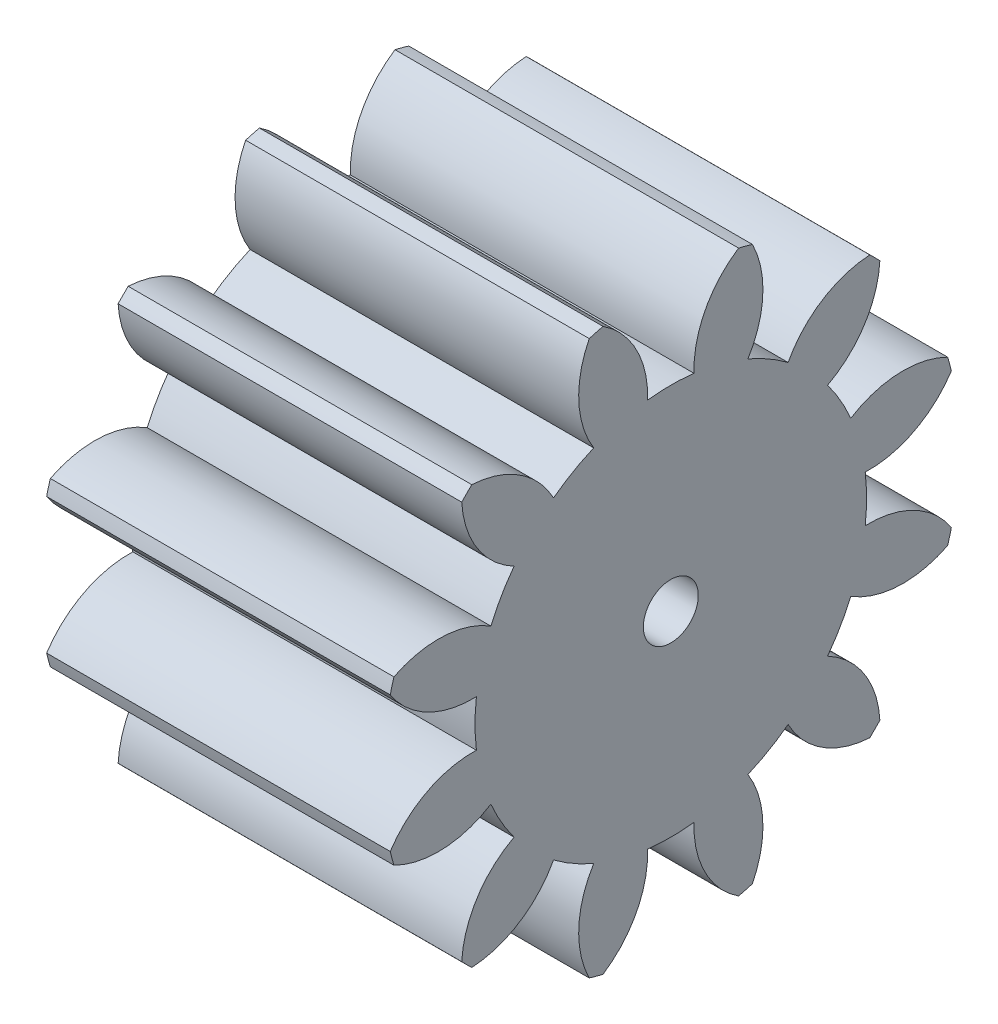
SolidWorks part; units mm, degrees
ref_plane "Plane1" through (0, 0, 0) normal (0, 0, 1) x (1, 0, 0)
ref_plane "Plane2" through (0, 0, 0) normal (0, 1, 0) x (1, 0, 0)
ref_plane "Plane3" through (0, 0, 0) normal (1, 0, 0) x (0, 0, -1)
other "Configuration Table"
sketch "HoldingSke" plane through (0, 0, 0) normal (0, 1, 0) x (1, 0, 0)
  line L0 (0, 0) -> (1.6302, -0.3465)
  line L1 (-15, 0) -> (100, 0) construction
  line L2 (0, 0) -> (-2.1039, 2.3779)
  line L3 (0, 0) -> (-11.863, 4.5341)
  line L4 (0, 0) -> (8.4473, 1.7955)
  line L5 (0, 0) -> (-46.8476, -17.4728)
  line L6 (0, 0) -> (-4.1448, -2.7965)
  line L7 (-2.1039, 2.3779) -> (8.6586, 51.2059)
  line L8 (-76.2, 54.61) -> (-76.1, 54.61)
  line L9 (-71.009, 38.7566) -> (-53.1078, 45.2721)
  line L10 (-76.2, 71.12) -> (104.1128, 71.12)
  line L11 (0, 0) -> (-5, 0)
  line L12 (-76.2, 101.6) -> (-76.177, 101.6)
  line L13 (24.9733, 27.94) -> (52.9518, 28.4284)
  line L14 (24.9733, 27.94) -> (24.9743, 27.94)
  line L15 (24.9733, 27.94) -> (100.4006, 29.5858)
  line L16 (-63.627, -0.6) -> (-12.827, -0.6)
  circle A0 centre (0, 0) radius 0.4
  circle A1 centre (0, 0) radius 2.849
  circle A2 centre (0, 0) radius 37.5
  circle A3 centre (0, 0) radius 0.4
  dimension "MHD" = 5.698
  dimension "Hub_dia" = 75
  dimension "Bore" = 0.8
  dimension "MBD" = 0.8
  dimension "Num_teeth" = 12
  dimension "Pitch" = 1.6667
  dimension "Overall_len" = 50
  dimension "Show_teeth" = 12
  dimension "Thickness" = 5
  dimension "OAL" = 50.0001
  dimension "T_dim" = 0.1
  dimension "Ap" = 20
  dimension "H" = 19.05
  dimension "Pitch_radius" = 180.3128
  dimension "Width" = 5
  dimension "Backlash" = 0.023
  dimension "Addendum_fac" = 1
  dimension "Dedendum_fac" = 1.25
  dimension "Clearance_fac" = 0.25
  dimension "Dedendum_add" = 0.001
  dimension "Module" = 0.6
sketch "BasProSke" plane through (0, 0, 0) normal (0, 1, 0) x (1, 0, 0)
  line L0 (-10, 0) -> (60, 0) construction
  line L1 (0, 0) -> (0, 4.2)
  line L2 (0, 0) -> (5, 0)
  line L3 (5, 0) -> (5, 4.2)
  line L4 (5, 4.2) -> (0, 4.2)
  dimension "Thickness" = 5
  dimension "Diameter" = 8.4
revolve "Base-Revolve" add sketch "BasProSke" angle 360 about L0
sketch "TooCutSke" plane through (0, 0, 0) normal (1, 0, 0) x (0, 0, -1)
  line L1 (0, 0) -> (0, 107) construction
  line L2 (0, 0) -> (-0.5101, 3.5637) construction
  line L3 (0, 0) -> (-1.8502, 6.905) construction
  line L4 (-0.5101, 3.5637) -> (-0.9251, 3.4525) construction
  arc A0 (0.3376, 2.8289) -> (-0.3376, 2.8289) centre (0, 0) ccw
  arc A1 (1.0161, 4.1014) -> (-1.0161, 4.1014) centre (0, 0) ccw
  circle A2 centre (0, 0) radius 3.6 construction
  circle A3 centre (0, 0) radius 3.3829 construction
  arc A4 (-0.3376, 2.8289) -> (-1.0161, 4.1014) centre (-1.7768, 2.8787) ccw
  arc A5 (1.0161, 4.1014) -> (0.3376, 2.8289) centre (1.7768, 2.8787) ccw
  dimension "Root_dia" = 5.698
  dimension "Overcut_dia" = 8.4508
  dimension "Pitch_dia" = 7.2
  dimension "Base_dia" = 6.7658
  dimension "Flank_rad" = 1.44
  dimension "Half_ang" = 15
  dimension "Half_CT" = 0.4296
extrude "ToothCut" cut sketch "TooCutSke" along normal through all
fillet "Breaks" [suppressed] radius 0.012
fillet "RootFillets" [suppressed] radius 0.151
pattern_circular "TeethCuts" count 12 every 30 about axis through (-10, 0, 0) along (1, 0, 0) of "ToothCut", "RootFillets", "Breaks"
sketch "HubNeaOneSke" plane through (0, 0, 0) normal (-1, 0, 0) x (0, 0, 1)
  circle A0 centre (0, 0) radius 2.849
  dimension "Diameter" = 5.698
extrude "HubNearOne" [suppressed] add sketch "HubNeaOneSke" along normal blind 45.0001
sketch "HubNeaBotSke" plane through (0, 0, 0) normal (-1, 0, 0) x (0, 0, 1)
  circle A0 centre (0, 0) radius 2.849
  dimension "Diameter" = 5.698
extrude "HubNearBoth" [suppressed] add sketch "HubNeaBotSke" along normal blind 22.5
ref_plane "FarPln" through (5, 0, 0) normal (1, 0, 0) x (0, 0, -1)
sketch "HubFarSke" plane through (5, 0, 0) normal (1, 0, 0) x (0, 0, -1)
  circle A0 centre (0, 0) radius 2.849
  dimension "Diameter" = 5.698
extrude "HubFar" [suppressed] add sketch "HubFarSke" along normal blind 22.5
sketch "BorSke" plane through (0, 0, 0) normal (1, 0, 0) x (0, 0, -1)
  circle A0 centre (0, 0) radius 0.4
  dimension "Diameter" = 0.8
extrude "Bore" cut sketch "BorSke" along normal mid plane 100.0001
sketch "KeySke" plane through (0, 0, 0) normal (1, 0, 0) x (0, 0, -1)
  line L0 (-0.05, 0) -> (-0.05, 0.5)
  line L1 (-0.05, 0.5) -> (0.05, 0.5)
  line L2 (0.05, 0.5) -> (0.05, 0)
  line L3 (0, 0) -> (0, 34) construction
  line L4 (-0.05, 0) -> (0.05, 0)
  dimension "Offset" = 0.5
  dimension "Width" = 0.1
extrude "Keyway" [suppressed] cut sketch "KeySke" along normal mid plane 100.0001
pattern_circular "Keyway2" [suppressed] count 2 every 90 about axis through (-10, 0, 0) along (1, 0, 0)
equation "' \"Module@HoldingSke\" = 6.35"
equation "' \"Num_teeth@HoldingSke\" = 12"
equation "' \"Ap@HoldingSke\" =  20"
equation "' \"Ap@HoldingSke\" = 20"
equation "' \"Width@HoldingSke\" = 0.5 * 25.4"
equation "' \"Hub_dia@HoldingSke\"= 1 * 25.4"
equation "' \"Hub_dia@HoldingSke\" = 1 * 25.4"
equation "' \"Overall_len@HoldingSke\" = 1.0 * 25.4"
equation "' \"Bore@HoldingSke\" = 0.75 * 25.4"
equation "' \"T_dim@HoldingSke\" = 0.1 * 25.4"
equation "' \"Width@KeySke\" = 0.25 * 25.4"
equation "' \"Show_teeth@HoldingSke\" = 13"
equation "' \"Backlash@HoldingSke\" = 0.009 * 25.4"
equation "' \"Addendum_fac@HoldingSke\" = 1.0"
equation "' \"Dedendum_fac@HoldingSke\" = 1.25"
equation "' \"Dedendum_add@HoldingSke\" = 0.00005 * 25.4"
equation "' \"Clearance_fac@HoldingSke\" = 0.25"
equation "\"Pitch@HoldingSke\" = 1 / \"Module@HoldingSke\""
equation "\"Overcut_dia@TooCutSke\" = (\"Num_teeth@HoldingSke\" + 2 * \"Addendum_fac@HoldingSke\") / \"Pitch@HoldingSke\" + 0.002 * 25.4"
equation "\"Pitch_dia@TooCutSke\" = \"Num_teeth@HoldingSke\" / \"Pitch@HoldingSke\""
equation "\"Base_dia@TooCutSke\" = \"Num_teeth@HoldingSke\" / \"Pitch@HoldingSke\" * cos((\"Ap@HoldingSke\"  * 3.14159265 / 180))"
equation "\"Root_dia@TooCutSke\" = (\"Num_teeth@HoldingSke\" + 2) / \"Pitch@HoldingSke\" - 2 * (\"Addendum_fac@HoldingSke\" + \"Dedendum_fac@HoldingSke\") / \"Pitch@HoldingSke\" - \"Dedendum_add@HoldingSke\" * 2"
equation "\"Half_ang@TooCutSke\" = 180 / \"Num_teeth@HoldingSke\""
equation "\"Half_CT@TooCutSke\" = \"Num_teeth@HoldingSke\" / \"Pitch@HoldingSke\" * sin((3.14159265 / 2 / \"Num_teeth@HoldingSke\")) / 2 - 7 * \"Backlash@HoldingSke\" / 4"
equation "\"Flank_rad@TooCutSke\" = \"Num_teeth@HoldingSke\" / \"Pitch@HoldingSke\" / 5"
equation "\"Radius@RootFillets\" = \"Clearance_fac@HoldingSke\" / \"Pitch@HoldingSke\" + \"Dedendum_add@HoldingSke\""
equation "\"Break_rad@Breaks\" = 0.02 / \"Pitch@HoldingSke\""
equation "\"Thickness@HoldingSke\" = \"Width@HoldingSke\""
equation "\"OAL@HoldingSke\" = \"Thickness@HoldingSke\""
equation "\"MHD@HoldingSke\" = (\"Num_teeth@HoldingSke\" + 2) / \"Pitch@HoldingSke\" - 2 * (\"Addendum_fac@HoldingSke\" + \"Dedendum_fac@HoldingSke\")  / \"Pitch@HoldingSke\" - \"Dedendum_add@HoldingSke\" * 2"
equation "\"MBD@HoldingSke\" = (\"Num_teeth@HoldingSke\" + 2) / \"Pitch@HoldingSke\" - 2 * (\"Addendum_fac@HoldingSke\" + \"Dedendum_fac@HoldingSke\")  / \"Pitch@HoldingSke\" - \"Dedendum_add@HoldingSke\" * 2 - 0.002 * 25.4"
equation "\"MHD@HoldingSke\" = ((sgn( \"MHD@HoldingSke\" - \"Hub_dia@HoldingSke\" )-1)*( \"MHD@HoldingSke\" - \"Hub_dia@HoldingSke\" ))/-2+ \"Hub_dia@HoldingSke\""
equation "\"MBD@HoldingSke\" = ((sgn( \"MBD@HoldingSke\" - \"Bore@HoldingSke\" )-1)*( \"MBD@HoldingSke\" - \"Bore@HoldingSke\" ))/-2+ \"Bore@HoldingSke\""
equation "\"OAL@HoldingSke\" = ((sgn( \"OAL@HoldingSke\" - \"Overall_len@HoldingSke\" )+1)*( \"OAL@HoldingSke\" - \"Overall_len@HoldingSke\" ))/2 + \"Overall_len@HoldingSke\" + 0.000002 * 25.4"
equation "\"Num_teeth@TeethCuts\" = int( \"Show_teeth@HoldingSke\" ) + 1"
equation "\"Num_teeth@TeethCuts\" = ((sgn( \"Num_teeth@TeethCuts\" - \"Num_teeth@HoldingSke\" )-1)*( \"Num_teeth@TeethCuts\" - \"Num_teeth@HoldingSke\" ))/-2+ \"Num_teeth@HoldingSke\""
equation "\"Num_teeth@TeethCuts\" = ((sgn( \"Num_teeth@TeethCuts\" - 2.0)+1)*( \"Num_teeth@TeethCuts\" - 2.0))/2 +2.0"
equation "\"Angle@TeethCuts\" = 360.0 / \"Num_teeth@HoldingSke\""
equation "\"Diameter@BasProSke\" = (\"Num_teeth@HoldingSke\" + 2 * \"Addendum_fac@HoldingSke\") / \"Pitch@HoldingSke\""
equation "\"Thickness@BasProSke\"  = \"Thickness@HoldingSke\""
equation "' \"Fillet_rad@BasProSke\" =  \"Thickness@HoldingSke\" * 0.05"
equation "' \"Fillet_rad@BasProSke\" = \"Thickness@HoldingSke\" * 0.05"
equation "\"MHD@HoldingSke\" = ((sgn( \"MHD@HoldingSke\" - \"Root_dia@TooCutSke\" )-1)*( \"MHD@HoldingSke\" - \"Root_dia@TooCutSke\" ))/-2+ \"Root_dia@TooCutSke\""
equation "\"Diameter@HubNeaOneSke\" = \"MHD@HoldingSke\""
equation "\"Length@HubNearOne\" = \"OAL@HoldingSke\" - \"Thickness@BasProSke\""
equation "\"Diameter@HubNeaBotSke\" = \"MHD@HoldingSke\""
equation "\"Length@HubNearBoth\" = ( \"OAL@HoldingSke\" - \"Thickness@BasProSke\" ) / 2.0"
equation "\"Thickness@FarPln\" = \"Thickness@BasProSke\""
equation "\"Diameter@HubFarSke\" = \"MHD@HoldingSke\""
equation "\"Length@HubFar\" = ( \"OAL@HoldingSke\" - \"Thickness@BasProSke\" ) / 2.0"
equation "\"Diameter@BorSke\" = \"MBD@HoldingSke\""
equation "\"D1@Bore\" = \"OAL@HoldingSke\" * 2.0"
equation "\"D1@Keyway\" = \"OAL@HoldingSke\" * 2.0"
equation "\"Offset@KeySke\" = \"T_dim@HoldingSke\" + \"MBD@HoldingSke\" / 2.0"
